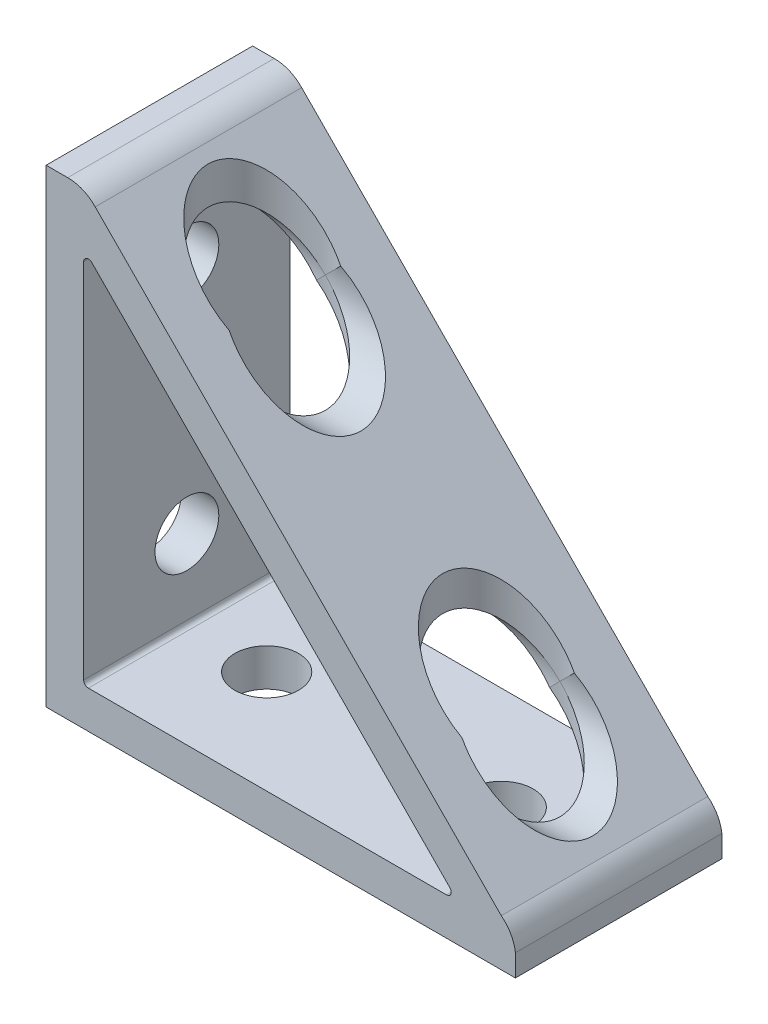
SolidWorks part; units mm, degrees
material "6105-T5 Aluminum"
ref_plane "Front Plane" through (0, 0, 0) normal (0, 0, 1) x (1, 0, 0)
ref_plane "Top Plane" through (0, 0, 0) normal (0, 1, 0) x (1, 0, 0)
ref_plane "Right Plane" through (0, 0, 0) normal (1, 0, 0) x (0, 0, -1)
sketch "Sketch1" plane through (0, 0, 0) normal (0, 0, 1) x (1, 0, 0)
  line L0 (0, 0) -> (50, 0)
  line L1 (0, 50) -> (2.3001, 50)
  line L2 (50, 2.3312) -> (50, 0)
  line L3 (4, 43.1058) -> (4, 4.5)
  line L4 (4.5, 4) -> (42.6627, 4)
  line L5 (5.2294, 48.7689) -> (48.5018, 4.9941)
  line L6 (4.8556, 43.4573) -> (43.0182, 4.8515)
  line L7 (0, 50) -> (0, 0)
  arc A0 (50, 2.3312) -> (48.5018, 4.9941) centre (46.0291, 1.85) ccw
  arc A1 (5.2294, 48.7689) -> (2.3001, 50) centre (2.3425, 46.0002) ccw
  arc A2 (4, 43.1058) -> (4.8556, 43.4573) centre (4.5, 43.1058) cw
  arc A3 (4, 4.5) -> (4.5, 4) centre (4.5, 4.5) ccw
  arc A4 (42.6627, 4) -> (43.0182, 4.8515) centre (42.6627, 4.5) ccw
  dimension "D3" = 4
  dimension "D4" = 4
  dimension "D5" = 0.5
  dimension "D6" = 0.5
  dimension "D7" = 0.5
  dimension "D11" = 90
  dimension "D1" = 50
  dimension "D2" = 50
  dimension "D8" = 4
  dimension "D9" = 4
  dimension "D10" = 4
extrude "Extrude1" add sketch "Sketch1" along normal blind 22
sketch "Sketch4" plane through (0, 50, 0) normal (0, 1, 0) x (1, 0, 0)
  line L1 (25, -22) -> (25, 0)
  line L2 (12.5, -22) -> (12.5, 0)
  line L3 (12.5, -22) -> (12.5, 0)
  line L4 (37.5, -22) -> (37.5, 0)
  circle A0 centre (12.5, -11) radius 3.4
  circle A1 centre (37.5, -11) radius 3.4
  dimension "D1" = 12.5
  dimension "D2" = 12.5
  dimension "D3" = 12.5
extrude "Cut-Extrude1" cut sketch "Sketch4" against normal through all contours A0 L3 | A0 L3 | A1 L4 | A1 L4
sketch "Sketch5" plane through (0, 50, 0) normal (0, 1, 0) x (1, 0, 0)
  circle A0 centre (12.5, -11) radius 6.25
  circle A1 centre (37.5, -11) radius 6.25
extrude "Cut-Extrude2" cut sketch "Sketch5" against normal up to surface (46 mm away) up to face at (34.1, 4, 11)
sketch "Sketch6" plane through (50, 0, 0) normal (1, 0, 0) x (0, 0, -1)
  line L2 (-22, 25) -> (0, 25)
  line L3 (-22, 12.5) -> (0, 12.5)
  line L4 (-22, 12.5) -> (0, 12.5)
  line L5 (-22, 37.5) -> (0, 37.5)
  circle A0 centre (-11, 12.5) radius 3.4
  circle A1 centre (-11, 37.5) radius 3.4
  dimension "D1" = 12.5
  dimension "D2" = 12.5
  dimension "D3" = 12.5
extrude "Cut-Extrude3" cut sketch "Sketch6" against normal through all contours L5 A1 | L5 A1 | L4 A0 | L4 A0
sketch "Sketch7" plane through (50, 0, 0) normal (1, 0, 0) x (0, 0, -1)
  circle A0 centre (-11, 12.5) radius 6.25
  circle A1 centre (-11, 37.5) radius 6.25
extrude "Cut-Extrude4" cut sketch "Sketch7" against normal up to surface (46 mm away) up to face at (4, 15.9, 11)
ref_plane "Plane1" through (0, 0, 11) normal (0, 0, 1) x (1, 0, 0)
